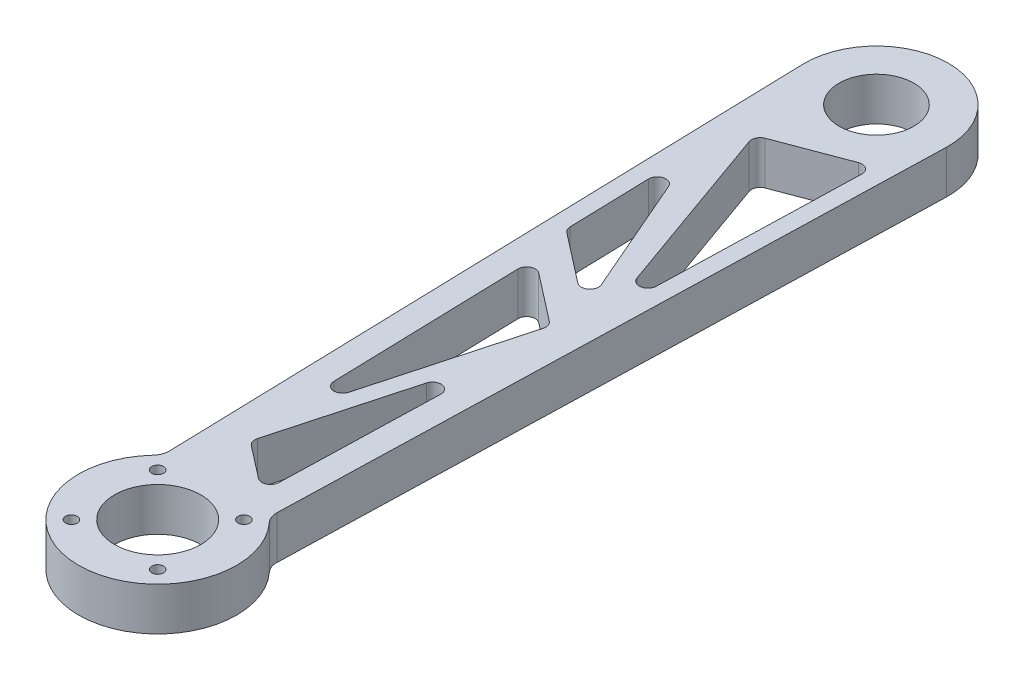
SolidWorks part; units mm, degrees
material "1060 合金"
ref_plane "前视基准面" through (0, 0, 0) normal (0, 0, 1) x (1, 0, 0)
ref_plane "上视基准面" through (0, 0, 0) normal (0, 1, 0) x (1, 0, 0)
ref_plane "右视基准面" through (0, 0, 0) normal (1, 0, 0) x (0, 0, -1)
sketch "草图1" plane through (0, 0, 0) normal (0, 1, 0) x (1, 0, 0)
  line L0 (0, 0) -> (0, 250) construction
  line L1 (-17.9929, -0.504) -> (-24.9902, 249.3)
  line L2 (17.9929, -0.504) -> (24.9902, 249.3)
  line L3 (-11.9953, -0.336) -> (-18.9926, 249.468) construction
  line L4 (11.9953, -0.336) -> (18.9926, 249.468) construction
  line L5 (-16.4444, 158.5) -> (15.7446, 133.5146) construction
  line L6 (15.7446, 133.5146) -> (18.4752, 231) construction
  line L7 (18.4752, 231) -> (-18.0888, 217.2024) construction
  line L8 (-18.0888, 217.2024) -> (-16.4444, 158.5) construction
  line L9 (15.7446, 133.5146) -> (-18.0888, 217.2024) construction
  line L10 (18.5259, 134.639) -> (-15.3075, 218.3268) construction
  line L11 (12.9633, 132.3901) -> (-20.8701, 216.0779) construction
  line L12 (-16.4444, 158.5) -> (-17.7049, 203.5)
  line L13 (-17.7049, 203.5) -> (11.0289, 137.1749)
  line L14 (11.0289, 137.1749) -> (-16.4444, 158.5)
  line L15 (15.9543, 141) -> (18.4752, 231)
  line L16 (-15.3075, 218.3268) -> (-18.4322, 226.0559) construction
  line L17 (18.4752, 231) -> (-12, 219.5)
  line L18 (-12, 219.5) -> (15.9543, 141)
  circle A0 centre (0, 250) radius 25 construction
  circle A1 centre (0, 0) radius 18 construction
  circle A2 centre (0, 0) radius 5.05
  circle A3 centre (0, 250) radius 13
  arc A4 (-17.9929, -0.504) -> (17.9929, -0.504) centre (0, 0) ccw
  arc A5 (-24.9902, 249.3) -> (24.9902, 249.3) centre (0, 250) cw
  arc A6 (-18.9926, 249.468) -> (18.9926, 249.468) centre (0, 250) cw construction
  arc A7 (-11.9953, -0.336) -> (11.9953, -0.336) centre (0, 0) ccw construction
  dimension "D2" = 50
  dimension "D3" = 36
  dimension "D4" = 10.1
  dimension "D5" = 26
  dimension "D1" = 250
  dimension "D9" = 19
  dimension "D10" = 30.5
  dimension "D11" = 16
  dimension "D12" = 45
  dimension "D13" = 90
  dimension "D14" = 12
  dimension "D6" = 6
  dimension "D7" = 3
  dimension "D8" = 3
extrude "凸台-拉伸1" add sketch "草图1" along normal blind 15
fillet "圆角1" radius 3 6 edges at (18.4752, 7.5, -231) (-12, 7.5, -219.5) (-17.7049, 7.5, -203.5) (-16.4444, 7.5, -158.5) (15.9543, 7.5, -141) (11.0289, 7.5, -137.1749)
sketch "草图2" plane through (0, 15, 0) normal (0, 1, 0) x (1, 0, 0)
  line L0 (0, 250) -> (-15, 250) construction
  circle A0 centre (-15, 250) radius 2
  dimension "D2" = 4
  dimension "D1" = 15
extrude "切除-拉伸1" [suppressed] cut sketch "草图2" against normal through all
pattern_circular "阵列(圆周)1" [suppressed] count 3 over 360
sketch "草图3" plane through (0, 15, 0) normal (0, 1, 0) x (1, 0, 0)
  line L0 (0, 250) -> (14.25, 250) construction
  circle A0 centre (14.25, 250) radius 2
  dimension "D2" = 4
  dimension "D1" = 14.25
extrude "切除-拉伸2" [suppressed] cut sketch "草图3" against normal through all
pattern_circular "阵列(圆周)2" [suppressed] count 3 over 360
sketch "草图4" plane through (0, 15, 0) normal (0, 1, 0) x (1, 0, 0)
  line L2 (8.9965, -0.252) -> (15.9937, 249.552)
  line L3 (8.9965, -0.252) -> (15.9937, 249.552) construction
  line L4 (-13.0503, 144.4724) -> (12.4949, 124.6439)
  line L5 (-15.9937, 249.552) -> (-8.9965, -0.252)
  line L6 (-15.9937, 249.552) -> (-8.9965, -0.252) construction
  line L7 (-15.3248, 157.6309) -> (1.7846, 144.3504) construction
  line L8 (12.4949, 124.6439) -> (9.7421, 26.3657)
  line L9 (9.7421, 26.3657) -> (-10.1751, 41.8256)
  line L10 (-10.1751, 41.8256) -> (-13.0503, 144.4724)
  dimension "D3" = 9
  dimension "D1" = 9
  dimension "D2" = 9
extrude "切除-拉伸3" cut sketch "草图4" against normal through all
fillet "圆角2" radius 3 3 edges at (9.7421, 7.5, -26.3657) (-10.1751, 7.5, -41.8256) (-13.0503, 7.5, -144.4724)
sketch "草图5" plane through (0, 15, 0) normal (0, 1, 0) x (1, 0, 0)
  circle A0 centre (0, 0) radius 27.5
  circle A1 centre (0, 0) radius 5.05
  dimension "D1" = 55
extrude "凸台-拉伸2" add sketch "草图5" against normal up to surface (15 mm away) up to face at (-1.8624, 0, -78.5335)
fillet "圆角3" radius 6 2 edges at (-18.5751, 7.5, -20.2785) (18.5751, 7.5, -20.2785)
sketch "草图6" plane through (0, 15, 0) normal (0, 1, 0) x (1, 0, 0)
  line L0 (12.4949, 124.6439) -> (-10.1751, 41.8256) construction
  line L1 (-12.8725, 138.1249) -> (-10.2148, 43.2424) construction
  line L2 (9.6014, 125.4359) -> (-13.0687, 42.6176)
  line L3 (15.3885, 123.8518) -> (-7.2816, 41.0335)
  line L4 (-7.2816, 41.0335) -> (-7.6098, 39.8344)
  line L5 (-7.6098, 39.8344) -> (-13.0687, 42.6176)
  line L6 (9.6014, 125.4359) -> (9.9296, 126.6351)
  line L7 (9.9296, 126.6351) -> (15.3885, 123.8518)
  line L8 (-9.0555, 40.9565) -> (5.0694, 29.9927) construction
  line L9 (12.4949, 124.6439) -> (-8.0342, 140.5788) construction
  dimension "D1" = 3
  dimension "D2" = 3
extrude "凸台-拉伸3" add sketch "草图6" against normal up to surface (15 mm away) up to face at (-1.8624, 0, -78.5335)
fillet "圆角4" radius 3 4 edges at (12.1404, 7.5, -111.9858) (-10.4638, 7.5, -52.1336) (9.9296, 7.5, -126.6351) (-7.6098, 7.5, -39.8344)
sketch "草图7" plane through (0, 15, 0) normal (0, 1, 0) x (1, 0, 0)
  line L1 (15, 15) -> (-15, 15) construction
  line L2 (15, 15) -> (15, -15) construction
  line L3 (15, -15) -> (-15, -15) construction
  line L4 (-15, 15) -> (-15, -15) construction
  circle A0 centre (0, 0) radius 5.05 construction
  circle A1 centre (15, 15) radius 2.05
  circle A2 centre (-15, 15) radius 2.05
  circle A3 centre (-15, -15) radius 2.05
  circle A5 centre (15, -15) radius 2.05
  dimension "D2" = 15
  dimension "D4" = 4.1
  dimension "D1" = 30
  dimension "D3" = 15
extrude "切除-拉伸4" cut sketch "草图7" against normal through all
sketch "草图8" plane through (0, 15, 0) normal (0, 1, 0) x (1, 0, 0)
  circle A0 centre (0, 0) radius 15
  dimension "D1" = 30
extrude "切除-拉伸5" cut sketch "草图8" against normal through all
